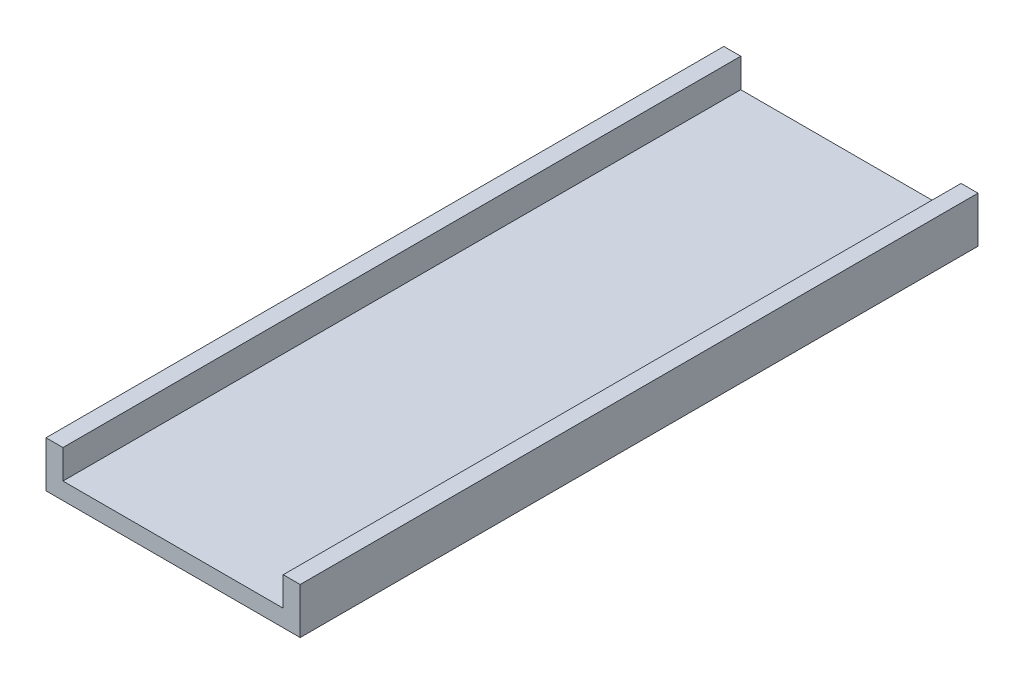
SolidWorks part; units mm, degrees
ref_plane "Plan de face" through (0, 0, 0) normal (0, 0, 1) x (1, 0, 0)
ref_plane "Plan de dessus" through (0, 0, 0) normal (0, 1, 0) x (1, 0, 0)
ref_plane "Plan de droite" through (0, 0, 0) normal (1, 0, 0) x (0, 0, -1)
sketch "Esquisse1" plane through (0, 0, 0) normal (0, 0, 1) x (1, 0, 0)
  line L0 (-27.2587, 5.4256) -> (-27.2587, 0)
  line L1 (-27.2587, 0) -> (2.7413, 0)
  line L2 (2.7413, 0) -> (2.7413, 5.4256)
  line L3 (-25.2587, 5.4256) -> (-25.2587, 2)
  line L4 (-25.2587, 2) -> (0.7413, 2)
  line L5 (0.7413, 2) -> (0.7413, 5.4256)
  line L6 (2.7413, 5.4256) -> (0.7413, 5.4256)
  line L7 (-25.2587, 5.4256) -> (-27.2587, 5.4256)
  dimension "D2" = 30
  dimension "D1" = 2
extrude "Boss.-Extru.1" add sketch "Esquisse1" along normal blind 95
sketch "Esquisse2" plane through (2.7413, 0, 0) normal (1, 0, 0) x (0, 0, -1)
  line L0 (-95, 5.4256) -> (0, 5.4256) construction
  line L1 (-95, 0) -> (-80, 0)
  line L2 (-95, 0) -> (-95, 5.4256)
  line L3 (-95, 5.4256) -> (-80, 5.4256)
  line L4 (-80, 0) -> (-80, 5.4256)
  dimension "D1" = 15
extrude "Enlèv. mat.-Extru.1" cut sketch "Esquisse2" against normal blind 46
